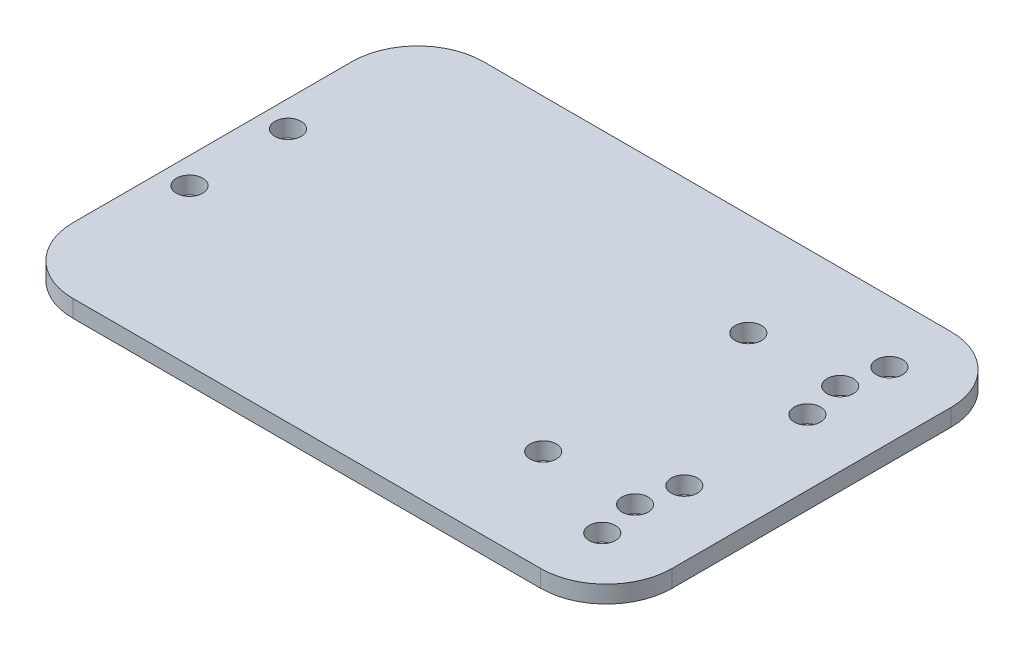
SolidWorks part; units mm, degrees
material "Hexcel AS4C (3000 丝)"
ref_plane "前视基准面" through (0, 0, 0) normal (0, 0, 1) x (1, 0, 0)
ref_plane "上视基准面" through (0, 0, 0) normal (0, 1, 0) x (1, 0, 0)
ref_plane "右视基准面" through (0, 0, 0) normal (1, 0, 0) x (0, 0, -1)
other "Configuration Table"
sketch "草图1" plane through (0, 0, 0) normal (0, 1, 0) x (1, 0, 0)
  line L1 (-36.5, -25) -> (36.5, -25)
  line L2 (-36.5, -25) -> (-36.5, 25)
  line L3 (-36.5, 25) -> (36.5, 25)
  line L4 (36.5, -25) -> (36.5, 25)
  line L5 (-36.5, -25) -> (36.5, 25) construction
  line L6 (-36.5, 25) -> (36.5, -25) construction
  point P0 (0, 0)
extrude "凸台-拉伸1" add sketch "草图1" along normal blind 2.1
sketch "草图2" plane through (0, 2.1, 0) normal (0, 1, 0) x (1, 0, 0)
  line L0 (-36.5, 0) -> (-33.3, 0)
  line L1 (-36.5, 25) -> (-36.5, -25) construction
  line L2 (-33.3, 6) -> (-33.3, -6)
  circle A0 centre (-33.3, 6) radius 1.6
  circle A1 centre (-33.3, -6) radius 1.6
  point P8 (-33.3, 0)
extrude "切除-拉伸1" cut sketch "草图2" against normal blind 2.1
sketch "草图3" plane through (0, 2.1, 0) normal (0, 1, 0) x (1, 0, 0)
  line L0 (36.5, -25) -> (36.5, 25) construction
  line L1 (36.5, 0) -> (36.5, 25)
  line L2 (36.5, 12.5) -> (28.5, 12.5)
  line L3 (36.5, 0) -> (36.5, -25)
  line L4 (36.5, -12.5) -> (28.5, -12.5)
  line L5 (28.5, 17.5) -> (28.5, 7.5)
  line L6 (28.5, -7.5) -> (28.5, -17.5)
  circle A0 centre (28.5, 17.5) radius 1.6
  circle A1 centre (28.5, 7.5) radius 1.6
  circle A2 centre (28.5, -7.5) radius 1.6
  circle A3 centre (28.5, -17.5) radius 1.6
  point P0 (36.5, 0)
  point P15 (28.5, 12.5)
  point P18 (28.5, -12.5)
extrude "切除-拉伸2" cut sketch "草图3" against normal blind 2.1
sketch "草图4" plane through (0, 2.1, 0) normal (0, 1, 0) x (1, 0, 0)
  line L0 (36.5, 0) -> (36.5, 25)
  line L1 (36.5, -25) -> (36.5, 25) construction
  line L2 (36.5, 0) -> (36.5, -25)
  line L3 (36.5, 12.5) -> (27.5, 12.5)
  line L4 (36.5, -12.5) -> (27.5, -12.5)
  line L5 (27.5, 12.5) -> (16.3, 12.5)
  line L6 (27.5, -12.5) -> (16.3, -12.5)
  circle A0 centre (16.3, 12.5) radius 1.6
  circle A1 centre (16.3, -12.5) radius 1.6
  circle A2 centre (27.5, 12.5) radius 1.6
  circle A3 centre (27.5, -12.5) radius 1.6
extrude "切除-拉伸3" cut sketch "草图4" against normal blind 2.1
fillet "圆角1" radius 8 4 edges at (-36.5, 1.05, 25) (-36.5, 1.05, -25) (36.5, 1.05, -25) (36.5, 1.05, 25)
